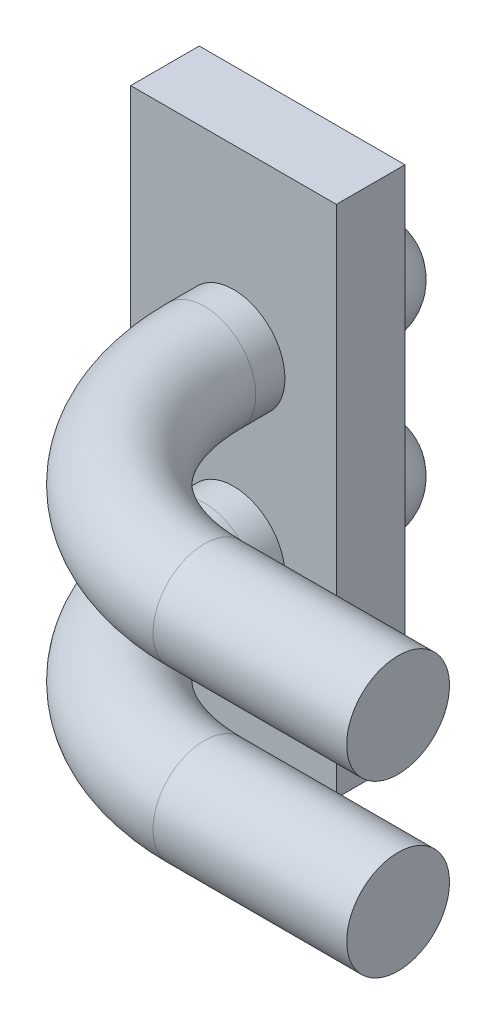
SolidWorks part; units mm, degrees
ref_plane "Front Plane" through (0, 0, 0) normal (0, 0, 1) x (1, 0, 0)
ref_plane "Top Plane" through (0, 0, 0) normal (0, 1, 0) x (1, 0, 0)
ref_plane "Right Plane" through (0, 0, 0) normal (1, 0, 0) x (0, 0, -1)
sketch "Sketch1" plane through (0, 0, 0) normal (0, 0, 1) x (1, 0, 0)
  line L1 (-3, -7.5) -> (3, -7.5)
  line L2 (-3, -7.5) -> (-3, 7.5)
  line L3 (-3, 7.5) -> (3, 7.5)
  line L4 (3, -7.5) -> (3, 7.5)
  line L5 (-3, -7.5) -> (3, 7.5) construction
  line L6 (-3, 7.5) -> (3, -7.5) construction
  point P0 (0, 0)
  dimension "D1" = 15
  dimension "D2" = 6
extrude "Boss-Extrude1" add sketch "Sketch1" along normal blind 2
sketch "Sketch2" plane through (0, 0, 0) normal (0, 0, -1) x (-1, 0, 0)
  circle A0 centre (0, 2.35) radius 1.5
  circle A1 centre (0, -2.62) radius 1.5
  dimension "D2" = 3
  dimension "D1" = 4.97
  dimension "D3" = 2.35
extrude "Boss-Extrude2" add sketch "Sketch2" along normal blind 3
fillet "Fillet1" radius 1.5 2 edges at (-1.5, -2.62, -3) (-1.5, 2.35, -3)
sketch "Sketch3" plane through (0, 0, 2) normal (0, 0, 1) x (1, 0, 0)
  circle A0 centre (0, -2.62) radius 1.5 construction
  circle A1 centre (0, 2.35) radius 1.5 construction
  circle A2 centre (0, -2.62) radius 1.5
  circle A3 centre (0, 2.35) radius 1.5
ref_plane "Plane1" through (0, 2.35, 0) normal (0, 1, 0) x (-1, 0, 0)
sketch "Sketch4" plane through (0, 2.35, 0) normal (0, 1, 0) x (-1, 0, 0)
  line L0 (0, 2) -> (0, 2.85)
  line L1 (1.5, 2) -> (-1.5, 2) construction
  line L2 (-6, 8.85) -> (-11.65, 8.85)
  arc A0 (0, 2.85) -> (-6, 8.85) centre (-6, 2.85) ccw
  point P8 (0, 8.85)
  dimension "D3" = 6
  dimension "D1" = 11.65
  dimension "D2" = 6.85
sweep "Sweep1" add profiles "Sketch3" path "Sketch4"
